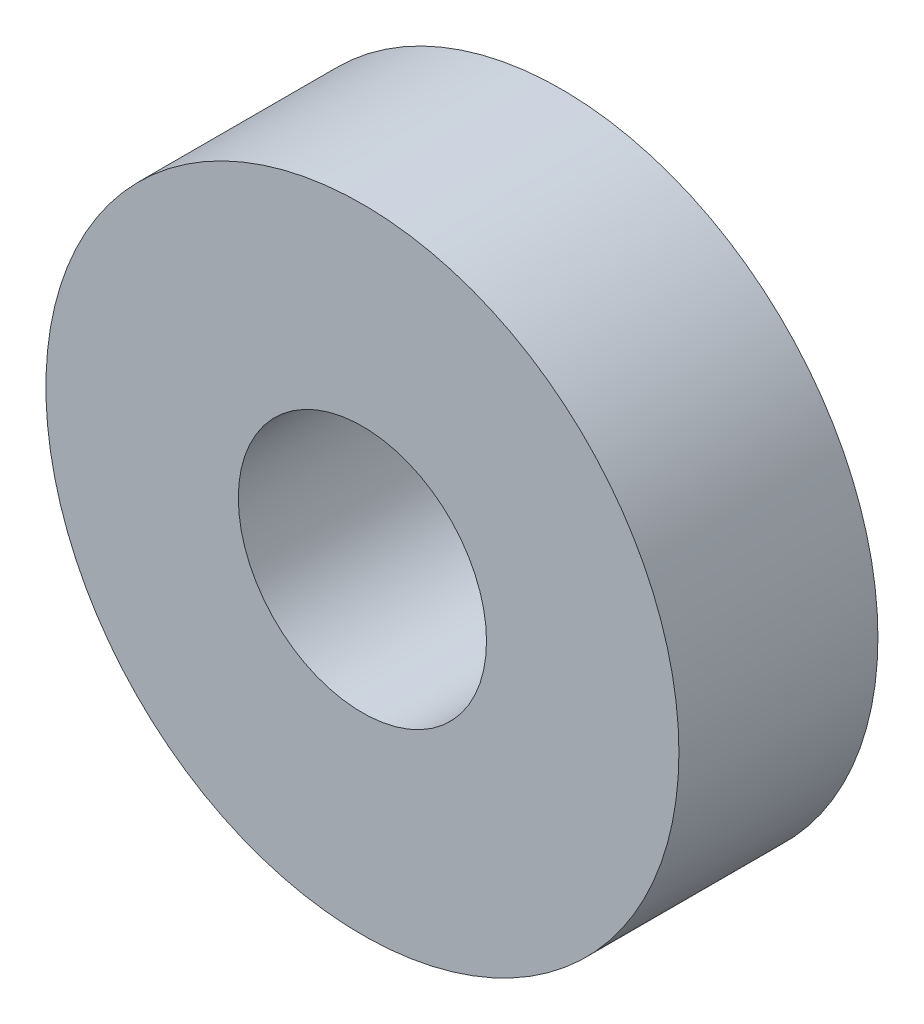
SolidWorks part; units mm, degrees
ref_plane "Plan de face" through (0, 0, 0) normal (0, 0, 1) x (1, 0, 0)
ref_plane "Plan de dessus" through (0, 0, 0) normal (0, 1, 0) x (1, 0, 0)
ref_plane "Plan de droite" through (0, 0, 0) normal (1, 0, 0) x (0, 0, -1)
sketch "Esquisse1" plane through (0, 0, 0) normal (0, 0, 1) x (1, 0, 0)
  circle A0 centre (0, 0) radius 10.1
  circle A1 centre (0, 0) radius 3.96
  dimension "D1" = 20.2
  dimension "D2" = 7.92
extrude "Boss.-Extru.1" add sketch "Esquisse1" along normal blind 6.35
